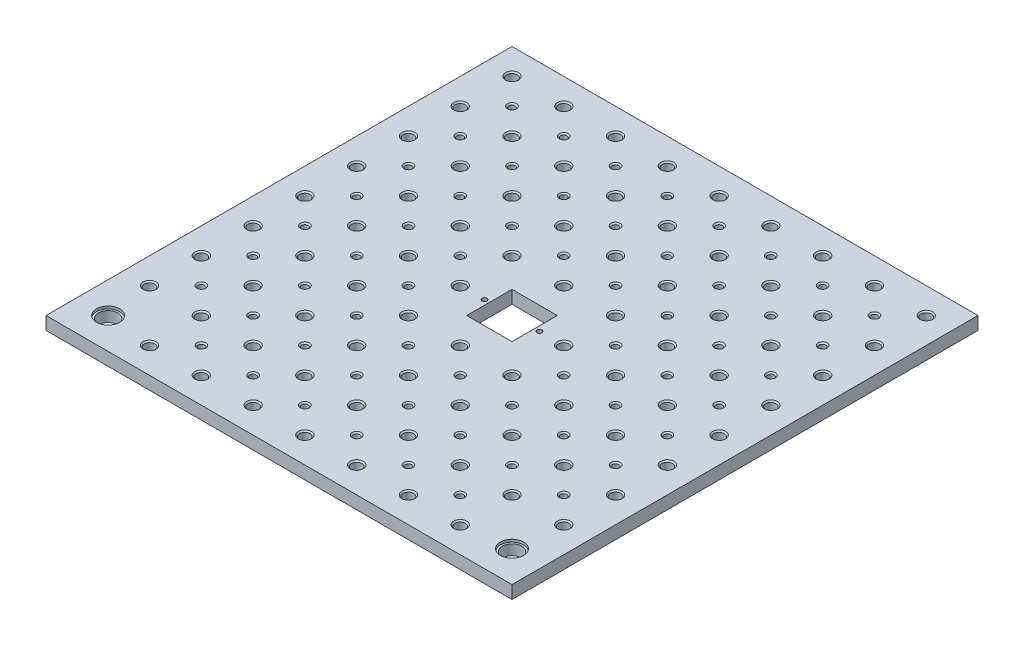
SolidWorks part; units mm, degrees
material "3D Printer - Undefined Plastic"
ref_plane "Front Plane" through (0, 0, 0) normal (0, 0, 1) x (1, 0, 0)
ref_plane "Top Plane" through (0, 0, 0) normal (0, 1, 0) x (1, 0, 0)
ref_plane "Right Plane" through (0, 0, 0) normal (1, 0, 0) x (0, 0, -1)
sketch "Sketch1" plane through (0, 0, 0) normal (0, 1, 0) x (1, 0, 0)
  line L1 (-114.3, -114.3) -> (114.3, -114.3)
  line L2 (-114.3, -114.3) -> (-114.3, 114.3)
  line L3 (-114.3, 114.3) -> (114.3, 114.3)
  line L4 (114.3, -114.3) -> (114.3, 114.3)
  line L5 (-114.3, -114.3) -> (114.3, 114.3) construction
  line L6 (-114.3, 114.3) -> (114.3, -114.3) construction
  point P0 (0, 0)
  dimension "D1" = 228.6
  dimension "D2" = 228.6
extrude "Boss-Extrude1" add sketch "Sketch1" along normal mid plane 6.35
sketch "Sketch2" plane through (0, 3.175, 0) normal (0, 1, 0) x (1, 0, 0)
  line L1 (-11.1125, -11.1125) -> (11.1125, -11.1125)
  line L2 (-11.1125, -11.1125) -> (-11.1125, 11.1125)
  line L3 (-11.1125, 11.1125) -> (11.1125, 11.1125)
  line L4 (11.1125, -11.1125) -> (11.1125, 11.1125)
  line L5 (-11.1125, -11.1125) -> (11.1125, 11.1125) construction
  line L6 (-11.1125, 11.1125) -> (11.1125, -11.1125) construction
  point P0 (0, 0)
  dimension "D1" = 22.225
  dimension "D2" = 22.225
extrude "Cut-Extrude1" cut sketch "Sketch2" against normal through all
hole_wizard "Bearing Mounting Pressfit Hole" positions "Sketch5" profile "Sketch6" counterbore size "3/8" standard "_Gentex Inch" end condition through all
sketch "Sketch5" plane through (0, 3.175, 0) normal (0, 1, 0) x (1, 0, 0)
  line L0 (-99.06, -99.06) -> (99.06, -99.06) construction
  line L2 (-99.06, -99.06) -> (-114.3, -99.06) construction
  line L3 (-114.3, 114.3) -> (-114.3, -114.3) construction
  line L5 (99.06, -99.06) -> (114.3, -99.06) construction
  line L6 (114.3, -114.3) -> (114.3, 114.3) construction
  line L9 (-114.3, -114.3) -> (114.3, -114.3) construction
  circle A0 centre (-99.06, -99.06) radius 15.24 construction
  point P0 (-99.06, -99.06)
  point P2 (99.06, -99.06)
  dimension "pulleyDiameter" = 30.48
  dimension "D1" = 15.24
sketch "Sketch6" plane through (-99.06, 3.175, 99.06) normal (1, 0, 0) x (0, 0, 1)
  line L0 (0, 0) -> (0, 6.35)
  line L1 (0, 6.35) -> (4.7625, 6.35)
  line L3 (4.7625, 6.35) -> (4.7625, 1.27)
  line L4 (4.7625, 1.27) -> (5.715, 1.27)
  line L5 (5.715, 1.27) -> (5.715, 0)
  line L7 (5.715, 0) -> (0, 0)
  line L11 (0, -6.35) -> (0, 107.95) construction
  dimension "Thru Hole Dia." = 9.525
  dimension "Thru Hole Depth" = 6.35
  dimension "C'Bore Dia." = 11.43
  dimension "C'Bore Depth" = 1.27
hole_wizard "Tapped Hole for #10-32 Helicoil1" positions "Sketch7" profile "Sketch8" tap size "#10-32" standard "Helicoil® Inch" end condition through all
sketch "Sketch7" plane through (0, 3.175, 0) normal (0, 1, 0) x (1, 0, 0)
  line L0 (-101.6, 101.6) -> (-101.6, 114.3) construction
  line L1 (114.3, 114.3) -> (-114.3, 114.3) construction
  line L3 (-101.6, 101.6) -> (-114.3, 101.6) construction
  line L4 (-114.3, 114.3) -> (-114.3, -114.3) construction
  point P6 (-101.6, 101.6)
  dimension "D1" = 12.7
sketch "Sketch8" plane through (-101.6, 3.175, -101.6) normal (1, 0, 0) x (0, 0, 1)
  line L0 (0, 0) -> (0, 6.35)
  line L1 (0, 6.35) -> (2.5527, 6.35)
  line L2 (2.5527, 6.35) -> (2.5527, 0.635)
  line L3 (2.5527, 0.635) -> (3.1877, 0)
  line L5 (3.1877, 0) -> (0, 0)
  line L6 (-2.5527, 0.635) -> (-3.1877, 0) construction
  line L11 (0, -6.35) -> (0, 107.95) construction
  dimension "Thru Tap Drill Dia." = 5.1054
  dimension "Thru Tap Drill Depth" = 6.35
  dimension "Near C'Sink Dia." = 6.3754
  dimension "Near C'Sink Angle" = 90
cosmetic thread "Hole Thread4" parameters "D1"=5.588, "D2"=5.936
hole_wizard "1/8 (0.1250) Dowel Hole1" positions "Sketch9" profile "Sketch10" hole size "1/8" standard "_Gentex Inch" end condition through all
sketch "Sketch9" plane through (0, 3.175, 0) normal (0, 1, 0) x (1, 0, 0)
  line L1 (-114.3, 114.3) -> (-88.9, 114.3)
  line L2 (-114.3, 114.3) -> (-114.3, 88.9)
  line L3 (-114.3, 88.9) -> (-88.9, 88.9)
  line L4 (-88.9, 114.3) -> (-88.9, 88.9)
  line L5 (-114.3, 114.3) -> (-88.9, 88.9) construction
  line L6 (-114.3, 88.9) -> (-88.9, 114.3) construction
  circle A0 centre (-101.6, 101.6) radius 3.1877 construction
  point P0 (-88.9, 88.9)
  point P79 (-101.6, 101.6)
sketch "Sketch10" plane through (-88.9, 3.175, -88.9) normal (1, 0, 0) x (0, 0, 1)
  line L0 (0, 0) -> (0, 6.35)
  line L1 (0, 6.35) -> (1.5875, 6.35)
  line L2 (1.5875, 6.35) -> (1.5875, 0.635)
  line L3 (1.5875, 0.635) -> (2.2225, 0)
  line L5 (2.2225, 0) -> (0, 0)
  line L6 (-1.5875, 0.635) -> (-2.2225, 0) construction
  line L11 (0, -6.35) -> (0, 107.95) construction
  dimension "Thru Hole Dia." = 3.175
  dimension "Thru Hole Depth" = 6.35
  dimension "Near C'Sink Dia." = 4.445
  dimension "Near C'Sink Angle" = 90
pattern_linear "Thread Hole Pattern" count 9 spacing 25.4 along (1, 0, 0) count 9 spacing 25.4 along (0, 0, 1) skipping (0, 8), (4, 4), (8, 8) of "Tapped Hole for #10-32 Helicoil1"
pattern_linear "Pin Hole Pattern" count 8 spacing 25.4 along (1, 0, 0) count 8 spacing 25.4 along (0, 0, 1) skipping (0, 7), (3, 3), (3, 4), (4, 3), (4, 4), (7, 7) of "1/8 (0.1250) Dowel Hole1"
hole_wizard "Tapped Hole for #2-56 Helicoil1" positions "Sketch11" profile "Sketch12" tap size "#2-56" standard "Helicoil® Inch" end condition through all
sketch "Sketch11" plane through (0, 3.175, 0) normal (0, 1, 0) x (1, 0, 0)
  line L0 (-3.4925, 0) -> (3.4925, 0) construction
  line L1 (-13.5, 0) -> (13.5, 0) construction
  point P0 (-13.5, 0)
  point P4 (13.5, 0)
  dimension "distanceSensorHoleWidth" = 27
cosmetic thread "Hole Thread1" parameters "D1"=2.54, "D2"=2.8372
cosmetic thread "Hole Thread2" parameters "D1"=2.54, "D2"=2.8372
sketch "Sketch12" plane through (-13.5, 3.175, 0) normal (1, 0, 0) x (0, 0, 1)
  line L0 (0, 0) -> (0, 6.35)
  line L1 (0, 6.35) -> (1.1913, 6.35)
  line L2 (1.1913, 6.35) -> (1.1913, 0)
  line L5 (1.1913, 0) -> (0, 0)
  line L11 (0, -6.35) -> (0, 107.95) construction
  dimension "Thru Tap Drill Dia." = 2.3825
  dimension "Thru Tap Drill Depth" = 6.35
